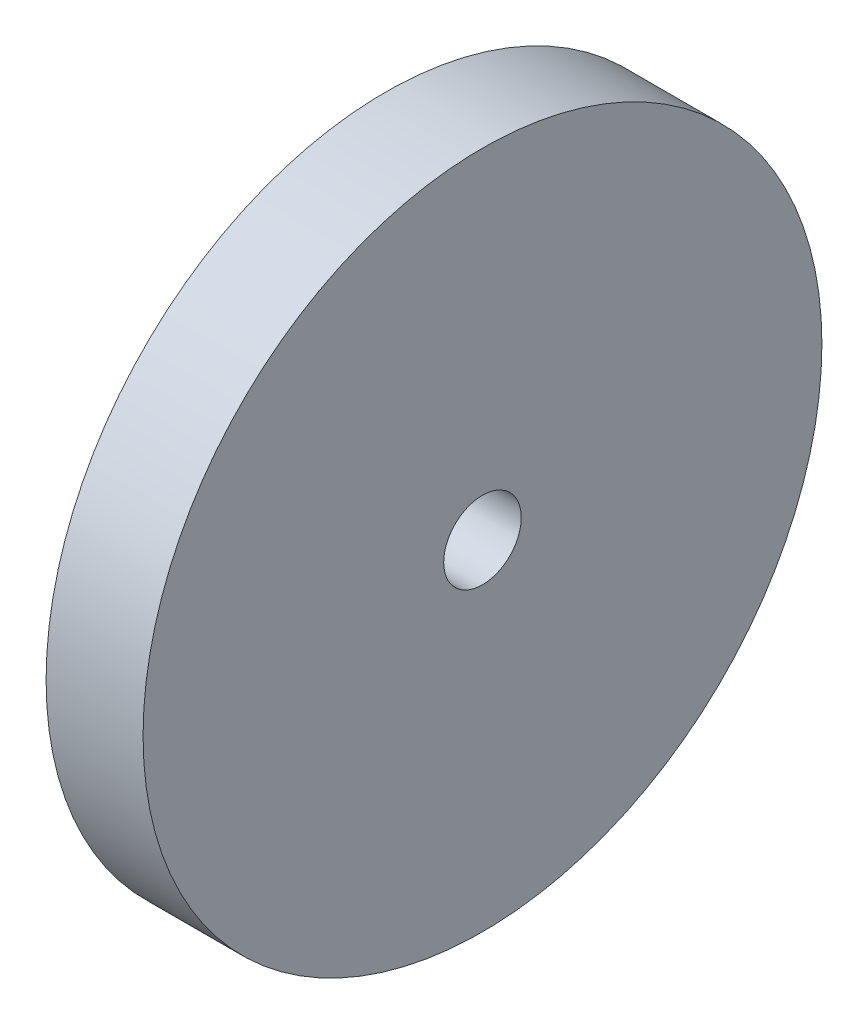
SolidWorks part; units mm, degrees
ref_plane "Front Plane" through (0, 0, 0) normal (0, 0, 1) x (1, 0, 0)
ref_plane "Top Plane" through (0, 0, 0) normal (0, 1, 0) x (1, 0, 0)
ref_plane "Right Plane" through (0, 0, 0) normal (1, 0, 0) x (0, 0, -1)
sketch "Sketch1" plane through (0, 0, 0) normal (0, 0, 1) x (1, 0, 0)
  line L0 (0, 0) -> (238.6577, 0) construction
  line L1 (0, 35) -> (10, 35)
  line L2 (10, 35) -> (10, 4)
  line L3 (10, 4) -> (0, 4)
  line L4 (0, 4) -> (0, 35)
  dimension "D1" = 70
  dimension "D2" = 8
  dimension "D3" = 10
revolve "Revolve1" add sketch "Sketch1" angle 360 about L0
